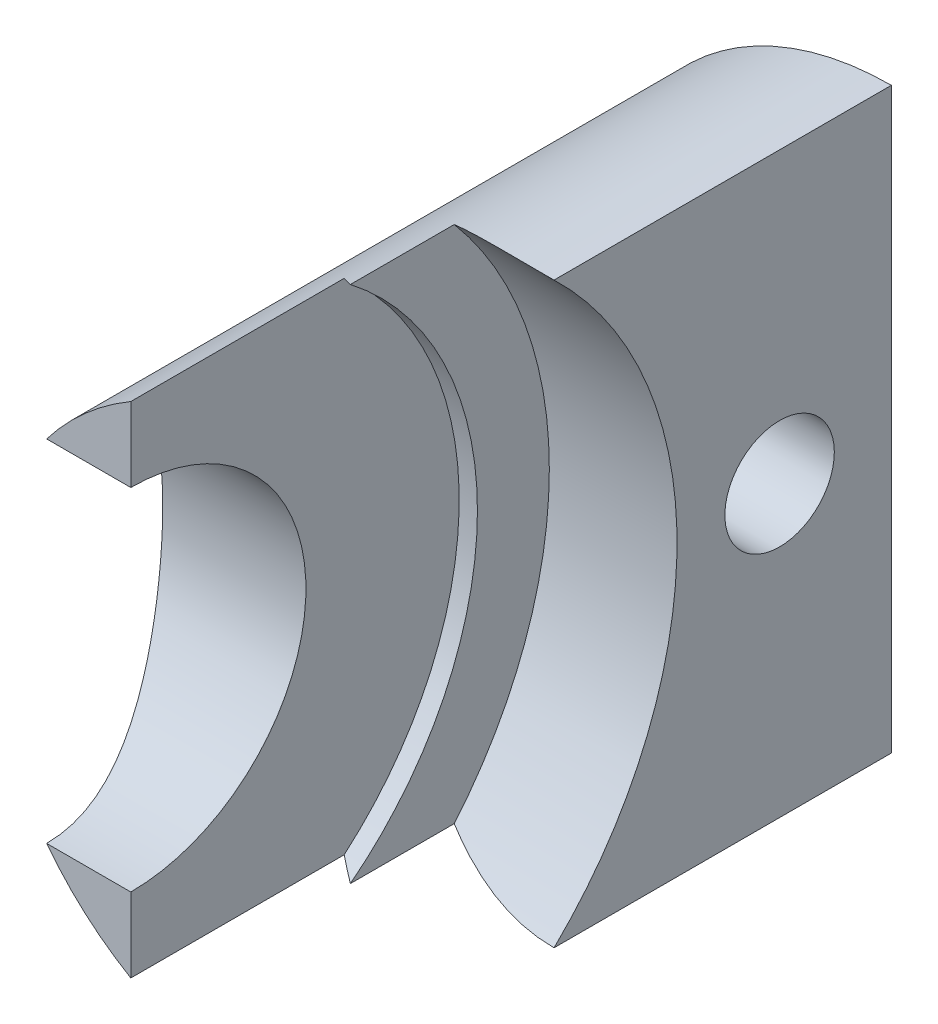
SolidWorks part; units mm, degrees
ref_plane "Front" through (0, 0, 0) normal (0, 0, 1) x (1, 0, 0)
ref_plane "Top" through (0, 0, 0) normal (0, 1, 0) x (1, 0, 0)
ref_plane "Right" through (0, 0, 0) normal (1, 0, 0) x (0, 0, -1)
sketch "Sketch1" plane through (0, 0, 0) normal (0, 0, 1) x (1, 0, 0)
  circle A0 centre (0, 0) radius 7.925
extrude "Extrude1" add sketch "Sketch1" along normal blind 16.8438
sketch "Sketch2" plane through (0, 0, 0) normal (0, 1, 0) x (1, 0, 0)
  line L2 (0, 0) -> (7.925, 0)
  line L4 (0, 0) -> (0, -17)
  line L7 (0, -17) -> (7.925, -17)
  line L8 (7.925, 0) -> (7.925, -17)
extrude "Cut-Extrude1" cut sketch "Sketch2" against normal through all and the other way through all
sketch "Sketch3" plane through (0, 0, 0) normal (1, 0, 0) x (0, 0, -1)
  line L0 (-16.8438, 0) -> (0, 0) construction
  circle A0 centre (-16.8731, 0) radius 11
extrude "Cut-Extrude2" cut sketch "Sketch3" against normal blind 3.5
sketch "Sketch6" plane through (0, 0, 0) normal (1, 0, 0) x (0, 0, -1)
  line L0 (-16.8438, 0) -> (0, 0) construction
  circle A0 centre (-16.8438, 0) radius 9
extrude "Cut-Extrude5" cut sketch "Sketch6" against normal blind 4
sketch "Sketch7" plane through (0, 0, 0) normal (1, 0, 0) x (0, 0, -1)
  line L0 (-16.8438, 0) -> (0, 0) construction
  circle A0 centre (-16.8438, 0) radius 4.8
  circle A1 centre (-3.0625, 0) radius 1.5
extrude "Cut-Extrude6" cut sketch "Sketch7" against normal through all
